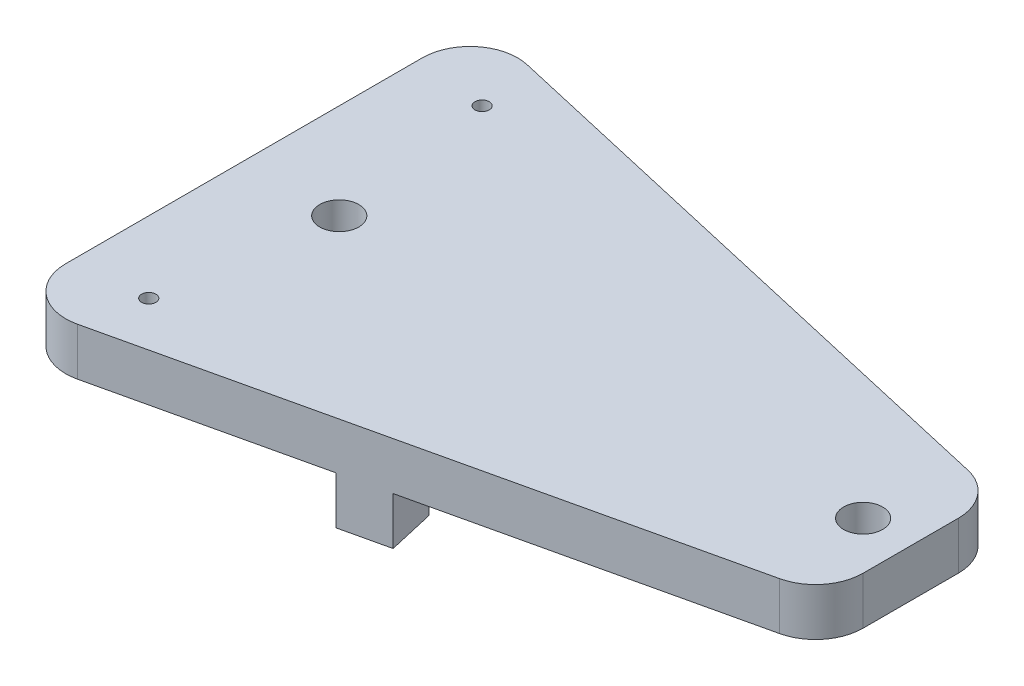
SolidWorks part; units mm, degrees
ref_plane "正面" through (0, 0, 0) normal (0, 0, 1) x (1, 0, 0)
ref_plane "平面" through (0, 0, 0) normal (0, 1, 0) x (1, 0, 0)
ref_plane "右側面" through (0, 0, 0) normal (1, 0, 0) x (0, 0, -1)
sketch "ｽｹｯﾁ1" plane through (0, 0, 0) normal (0, 1, 0) x (1, 0, 0)
  line L0 (-102.9858, 0) -> (37.0142, 0) construction
  line L1 (-90.7556, -47.202) -> (29.2444, -19.7481)
  line L2 (-102.9858, -37.4538) -> (-102.9858, 37.4538)
  line L3 (-90.7556, 47.202) -> (29.2444, 19.7481)
  line L4 (37.0142, -10) -> (37.0142, 10)
  line L5 (-102.9858, -50) -> (37.0142, 17.9705) construction
  line L6 (-102.9858, 50) -> (37.0142, -17.9705) construction
  circle A0 centre (-82.9858, 0) radius 4.1
  circle A1 centre (27.0142, 0) radius 4.1
  arc A2 (29.2444, 19.7481) -> (37.0142, 10) centre (27.0142, 10) cw
  arc A3 (29.2444, -19.7481) -> (37.0142, -10) centre (27.0142, -10) ccw
  arc A4 (-90.7556, -47.202) -> (-102.9858, -37.4538) centre (-92.9858, -37.4538) cw
  arc A5 (-102.9858, 37.4538) -> (-90.7556, 47.202) centre (-92.9858, 37.4538) cw
  circle A6 centre (-87.9858, 35) radius 1.5
  circle A7 centre (-87.9858, -35) radius 1.5
  point P0 (0, 0)
  point P28 (0, 0)
  dimension "D3" = 8.2
  dimension "D6" = 10
  dimension "D7" = 3
  dimension "D2" = 100
  dimension "D4" = 20
  dimension "D5" = 10
  dimension "D8" = 15
  dimension "D9" = 15
  dimension "D10" = 15
  dimension "D11" = 20
  dimension "D12" = 140
extrude "ﾎﾞｽ - 押し出し1" add sketch "ｽｹｯﾁ1" along normal blind 10
sketch "ｽｹｯﾁ2" plane through (0, 0, 0) normal (0, -1, 0) x (1, 0, 0)
  line L1 (-93.0858, 29.9) -> (-82.8858, 29.9)
  line L2 (-93.0858, 29.9) -> (-93.0858, 40.1)
  line L3 (-93.0858, 40.1) -> (-82.8858, 40.1)
  line L4 (-82.8858, 29.9) -> (-82.8858, 40.1)
  line L5 (-93.0858, 29.9) -> (-82.8858, 40.1) construction
  line L6 (-93.0858, 40.1) -> (-82.8858, 29.9) construction
  line L7 (-93.0858, -40.1) -> (-82.8858, -40.1)
  line L8 (-93.0858, -40.1) -> (-93.0858, -29.9)
  line L9 (-93.0858, -29.9) -> (-82.8858, -29.9)
  line L10 (-82.8858, -40.1) -> (-82.8858, -29.9)
  line L11 (-93.0858, -40.1) -> (-82.8858, -29.9) construction
  line L12 (-93.0858, -29.9) -> (-82.8858, -40.1) construction
  point P0 (-87.9858, 35)
  point P6 (-87.9858, -35)
  dimension "D1" = 10.2
extrude "ｶｯﾄ - 押し出し1" cut sketch "ｽｹｯﾁ2" against normal blind 5
sketch "ｽｹｯﾁ3" plane through (0, 0, 0) normal (0, -1, 0) x (1, 0, 0)
  line L0 (-46.5667, 37.0923) -> (-36.8185, 34.8621)
  line L1 (-90.7556, 47.202) -> (29.2444, 19.7481) construction
  line L2 (-36.8185, 34.8621) -> (-39.0487, 25.114)
  line L3 (-39.0487, 25.114) -> (-48.7969, 27.3442)
  line L4 (-48.7969, 27.3442) -> (-46.5667, 37.0923)
  line L5 (-46.5667, -37.0923) -> (-36.8185, -34.8621)
  line L6 (29.2444, -19.7481) -> (-90.7556, -47.202) construction
  line L7 (-36.8185, -34.8621) -> (-39.0487, -25.114)
  line L8 (-39.0487, -25.114) -> (-48.7969, -27.3442)
  line L9 (-48.7969, -27.3442) -> (-46.5667, -37.0923)
  arc A1 (-34.0468, 34.228) -> (-34.0468, -34.228) centre (27.0142, 0) ccw construction
  point P17 (0, 0)
  dimension "D3" = 70
  dimension "D1" = 10
  dimension "D2" = 10
extrude "ﾎﾞｽ - 押し出し2" add sketch "ｽｹｯﾁ3" along normal blind 10
